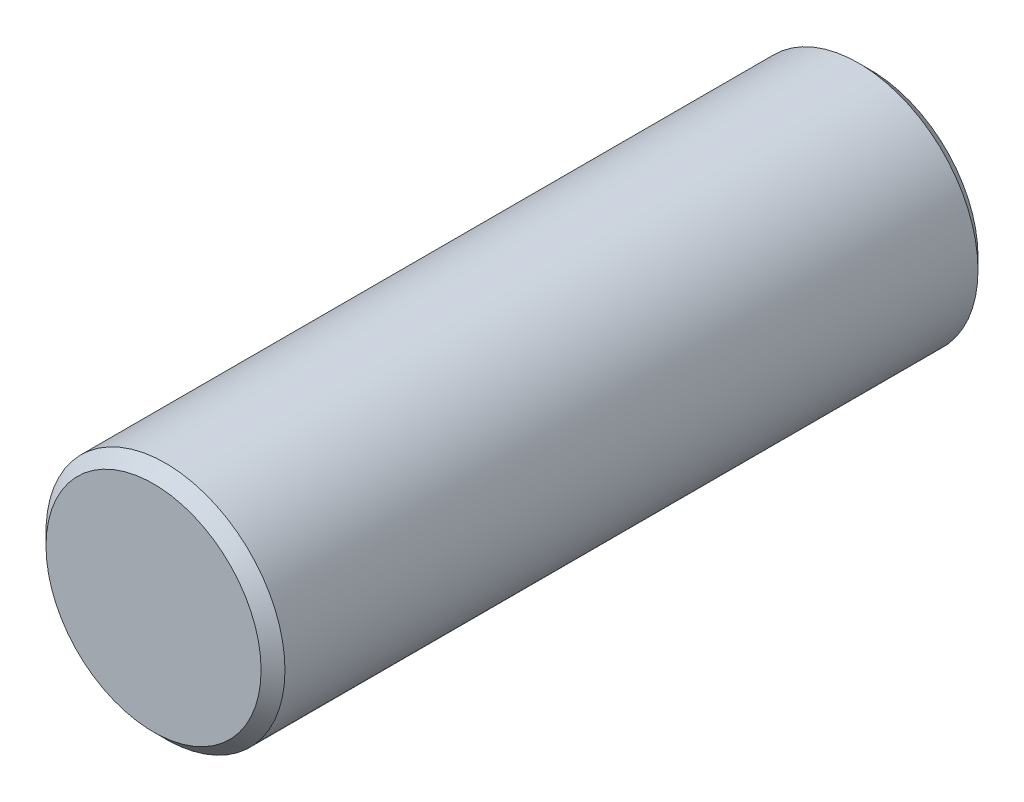
SolidWorks part; units mm, degrees
ref_plane "Спереди" through (0, 0, 0) normal (0, 0, 1) x (1, 0, 0)
ref_plane "Сверху" through (0, 0, 0) normal (0, 1, 0) x (1, 0, 0)
ref_plane "Справа" through (0, 0, 0) normal (1, 0, 0) x (0, 0, -1)
sketch "Эскиз1" plane through (0, 0, 0) normal (0, 0, 1) x (1, 0, 0)
  circle A0 centre (0, 0) radius 10
  dimension "D1" = 20
extrude "Бобышка-Вытянуть1" add sketch "Эскиз1" along normal blind 60
chamfer "Фаска1" distance 1 angle 45 2 edges at (10, 0, 0) (10, 0, 60)
